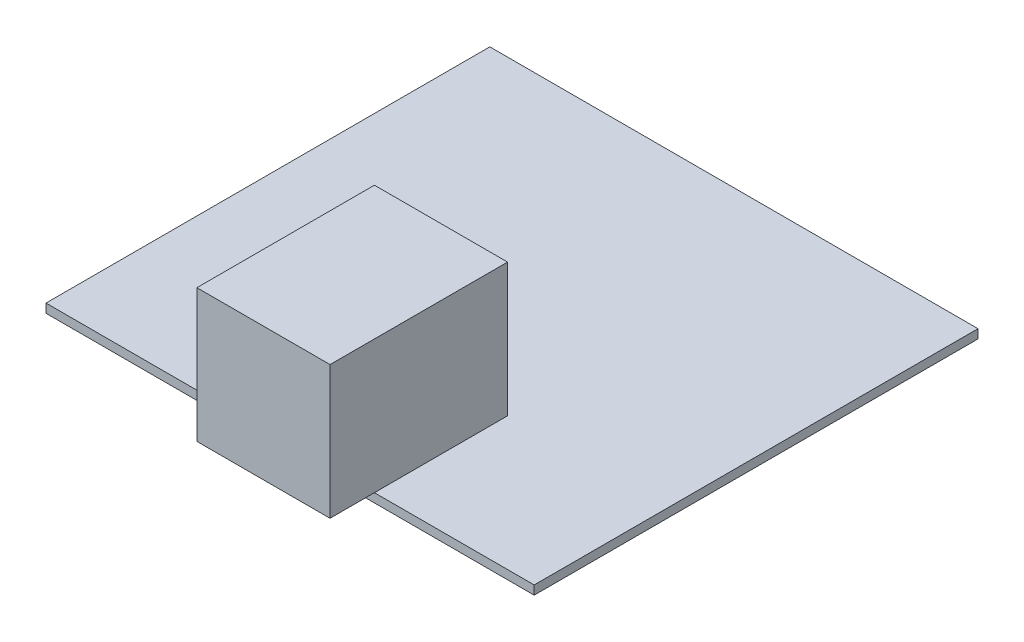
SolidWorks part; units mm, degrees
ref_plane "前视基准面" through (0, 0, 0) normal (0, 0, 1) x (1, 0, 0)
ref_plane "上视基准面" through (0, 0, 0) normal (0, 1, 0) x (1, 0, 0)
ref_plane "右视基准面" through (0, 0, 0) normal (1, 0, 0) x (0, 0, -1)
other "Configuration Table"
sketch "草图1" plane through (0, 0, 0) normal (0, 1, 0) x (1, 0, 0)
  line L1 (-27.9568, 19.2774) -> (27.0432, 19.2774)
  line L2 (-27.9568, 19.2774) -> (-27.9568, -30.7226)
  line L3 (-27.9568, -30.7226) -> (27.0432, -30.7226)
  line L4 (27.0432, 19.2774) -> (27.0432, -30.7226)
  dimension "D1" = 55
  dimension "D2" = 50
extrude "凸台-拉伸1" add sketch "草图1" along normal blind 1 contours L2 L1 L4 L3
sketch "草图2" plane through (0, 1, 0) normal (0, 1, 0) x (1, 0, 0)
  line L0 (-27.9568, -30.7226) -> (27.0432, -30.7226) construction
  line L1 (-5.9568, -15.7226) -> (9.0432, -15.7226)
  line L2 (-5.9568, -15.7226) -> (-5.9568, -35.7226)
  line L3 (-5.9568, -35.7226) -> (9.0432, -35.7226)
  line L4 (9.0432, -15.7226) -> (9.0432, -35.7226)
  line L5 (27.0432, 19.2774) -> (27.0432, -30.7226) construction
  dimension "D1" = 15
  dimension "D2" = 5
  dimension "20" = 20
  dimension "D3" = 18
extrude "凸台-拉伸2" add sketch "草图2" along normal blind 15 contours L2 L1 L4 L3
sketch "草图11" plane through (0, 0, 0) normal (0, -1, 0) x (-1, 0, 0)
  line L0 (27.9568, 19.2774) -> (-27.0432, 19.2774) construction
  line L1 (22.4515, 14.2774) -> (-21.3485, 14.2774)
  line L2 (22.4515, 14.2774) -> (22.4515, 19.2774)
  line L3 (22.4515, 19.2774) -> (-21.3485, 19.2774)
  line L4 (-21.3485, 14.2774) -> (-21.3485, 19.2774)
  dimension "D1" = 43.8
  dimension "D2" = 5
extrude "凸台-拉伸7" add sketch "草图11" along normal blind 5 contours L2 L1 L4 L3
sketch "草图12" plane through (0, -5, 0) normal (0, -1, 0) x (-1, 0, 0)
  line L0 (22.4515, 14.2774) -> (22.4515, 19.2774) construction
  line L1 (22.4515, 14.2774) -> (-21.3485, 14.2774) construction
  circle A0 centre (21.4515, 15.2774) radius 0.2
  dimension "D1" = 1
  dimension "D2" = 1
extrude "切除-拉伸1" cut sketch "草图12" against normal blind 5
pattern_linear "阵列(线性)1" count 20 spacing 2.2 along (1, 0, 0) count 2 spacing 3 along (0, 0, -1) of "切除-拉伸1"
